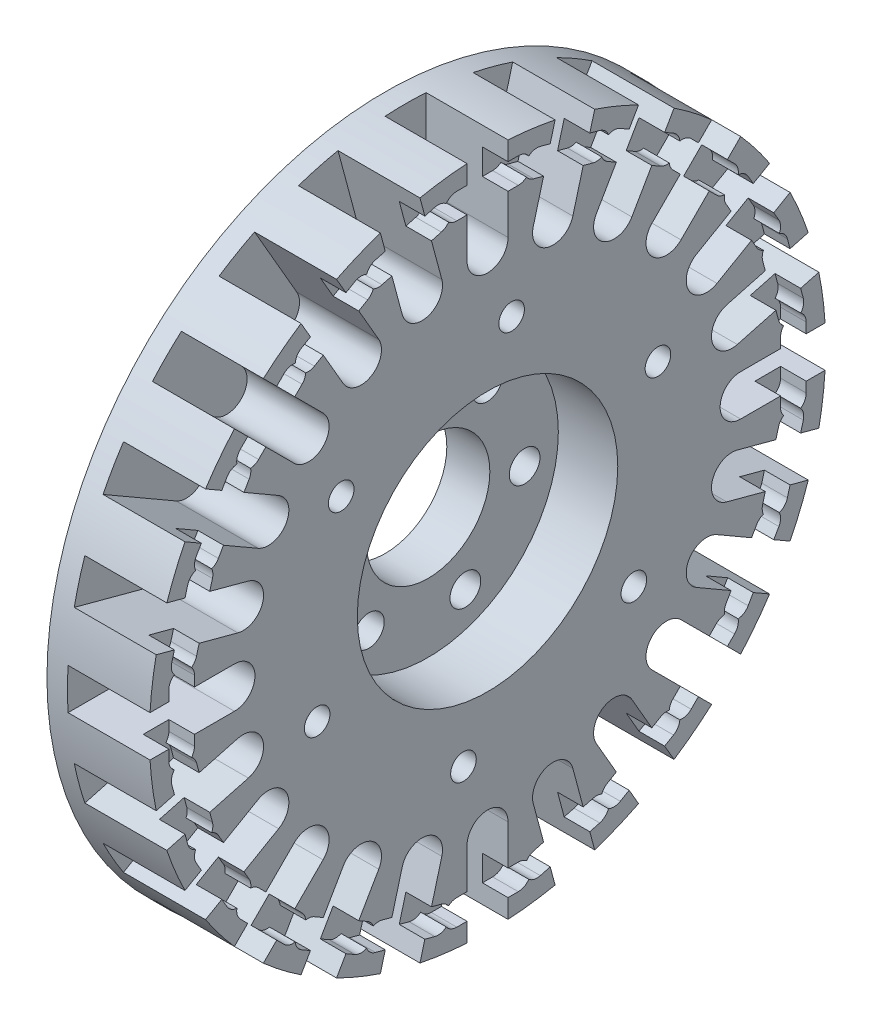
SolidWorks part; units mm, degrees
material "1060 Alloy"
ref_plane "Front Plane" through (0, 0, 0) normal (0, 0, 1) x (1, 0, 0)
ref_plane "Top Plane" through (0, 0, 0) normal (0, 1, 0) x (1, 0, 0)
ref_plane "Right Plane" through (0, 0, 0) normal (1, 0, 0) x (0, 0, -1)
sketch "Sketch1" plane through (0, 0, 0) normal (1, 0, 0) x (0, 0, -1)
  circle A0 centre (0, 0) radius 33
  circle A1 centre (0, 0) radius 6.025
  dimension "D1" = 66
  dimension "D2" = 12.05
extrude "Boss-Extrude1" add sketch "Sketch1" along normal blind 10
sketch "Sketch2" plane through (10, 0, 0) normal (1, 0, 0) x (0, 0, -1)
  line L0 (-2, 33) -> (2, 33)
  line L1 (2, 33) -> (2, 24.7)
  line L2 (-2, 24.7) -> (-2, 33)
  arc A0 (2, 24.7) -> (-2, 24.7) centre (0, 24.7) cw
  circle A1 centre (0, 0) radius 33 construction
  dimension "D1" = 4
  dimension "D2" = 8.3
extrude "Cut-Extrude1" cut sketch "Sketch2" against normal blind 8
sketch "Sketch3" plane through (10, 0, 0) normal (1, 0, 0) x (0, 0, -1)
  line L0 (-3, 29.85) -> (3, 29.85) construction
  line L1 (-3, 31.1) -> (3, 31.1)
  line L2 (-3, 28.6) -> (3, 28.6)
  arc A0 (-3, 31.1) -> (-3, 28.6) centre (-3, 29.85) ccw
  arc A1 (3, 28.6) -> (3, 31.1) centre (3, 29.85) ccw
  arc A2 (-2, 24.7) -> (2, 24.7) centre (0, 24.7) ccw construction
  point P2 (0, 29.85)
  dimension "D1" = 1.25
  dimension "D2" = 5.15
  dimension "D3" = 6
extrude "Cut-Extrude2" cut sketch "Sketch3" against normal blind 2.5
pattern_circular "CirPattern1" count 24 over 360 about axis through (0, 0, 0) along (1, 0, 0) of "Cut-Extrude1", "Cut-Extrude2"
hole_wizard "Tap Drill for M3x0.5 Tap1" positions "Sketch6" profile "Sketch5" hole size "M3x0.5" standard "ANSI Metric" end condition up to next
sketch "Sketch6" plane through (10, 0, 0) normal (1, 0, 0) x (0, 0, -1)
  line L0 (2.3495, 17.846) -> (0, 0) construction
  line L1 (0, 0) -> (6.025, 0) construction
  circle A2 centre (0, 0) radius 6.025 construction
  point P0 (2.3495, 17.846)
  dimension "D1" = 82.5
  dimension "D2" = 18
sketch "Sketch5" plane through (10, 17.846, -2.3495) normal (0, 1, 0) x (0, 0, -1)
  line L0 (0, 0) -> (0, 10.001)
  line L1 (0, 10.001) -> (1.25, 10.001)
  line L2 (1.25, 10.001) -> (1.25, 0)
  line L5 (1.25, 0) -> (0, 0)
  line L11 (0, -6.35) -> (0, 107.95) construction
  dimension "Thru Hole Dia." = 2.5
  dimension "Thru Hole Depth" = 10.001
pattern_circular "CirPattern2" count 6 over 360 about axis through (0, 0, 0) along (1, 0, 0) of "Tap Drill for M3x0.5 Tap1"
sketch "Sketch7" plane through (10, 0, 0) normal (-1, 0, 0) x (0, 0, 1)
  circle A0 centre (0, 0) radius 12.71
  dimension "D1" = 25.42
extrude "Cut-Extrude3" cut sketch "Sketch7" along normal offset from surface (5.8 mm away) 4.2 up to face at (0, 6.8883, -17.8798)
sketch "Sketch11" plane through (10, 0, 0) normal (1, 0, 0) x (0, 0, -1)
  line L0 (0, 0) -> (-10.5081, 0) construction
  line L1 (-3.6355, 8.7769) -> (0, 0) construction
  circle A0 centre (-3.6355, 8.7769) radius 1.5
  dimension "D1" = 3
  dimension "D2" = 9.5
  dimension "D3" = 67.5
extrude "Cut-Extrude4" cut sketch "Sketch11" against normal up to next
chamfer "Chamfer1" distance 1.5 angle 45 1 edges at (0, 8.7769, 2.1355)
pattern_circular "CirPattern3" count 6 over 360 about axis through (0, 0, 0) along (1, 0, 0) of "Cut-Extrude4", "Chamfer1"
